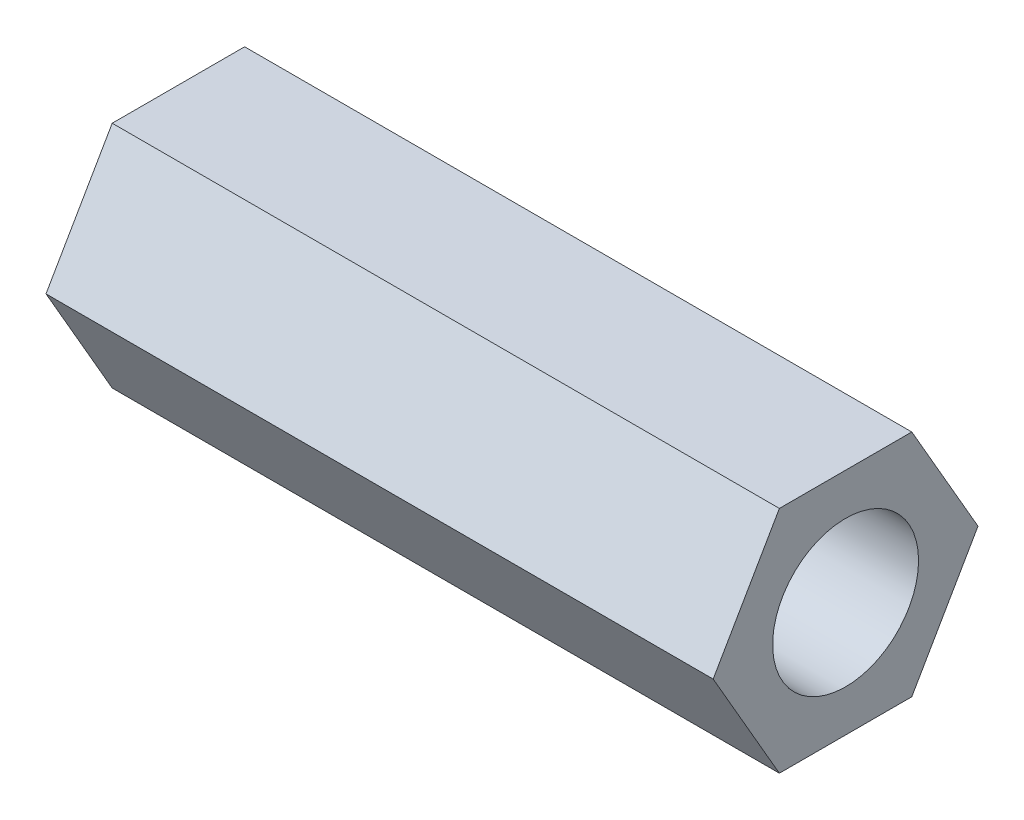
SolidWorks part; units mm, degrees
material "AISI 316 Annealed Stainless Steel Bar (SS)"
ref_plane "Front Plane" through (0, 0, 0) normal (0, 0, 1) x (1, 0, 0)
ref_plane "Top Plane" through (0, 0, 0) normal (0, 1, 0) x (1, 0, 0)
ref_plane "Right Plane" through (0, 0, 0) normal (1, 0, 0) x (0, 0, -1)
sketch "Sketch1" plane through (0, 0, 0) normal (1, 0, 0) x (0, 0, -1)
  line L1 (-10.082, 0) -> (-5.041, -8.7312)
  line L2 (-5.041, -8.7312) -> (5.041, -8.7312)
  line L3 (5.041, -8.7312) -> (10.082, 0)
  line L4 (10.082, 0) -> (5.041, 8.7313)
  line L5 (5.041, 8.7313) -> (-5.041, 8.7313)
  line L6 (-5.041, 8.7313) -> (-10.082, 0)
  circle A0 centre (0, 0) radius 8.7312 construction
  circle A1 centre (0, 0) radius 5.5562
  dimension "D1" = 11.1125
  dimension "D2" = 3.175
extrude "Boss-Extrude1" add sketch "Sketch1" along normal blind 50.8
